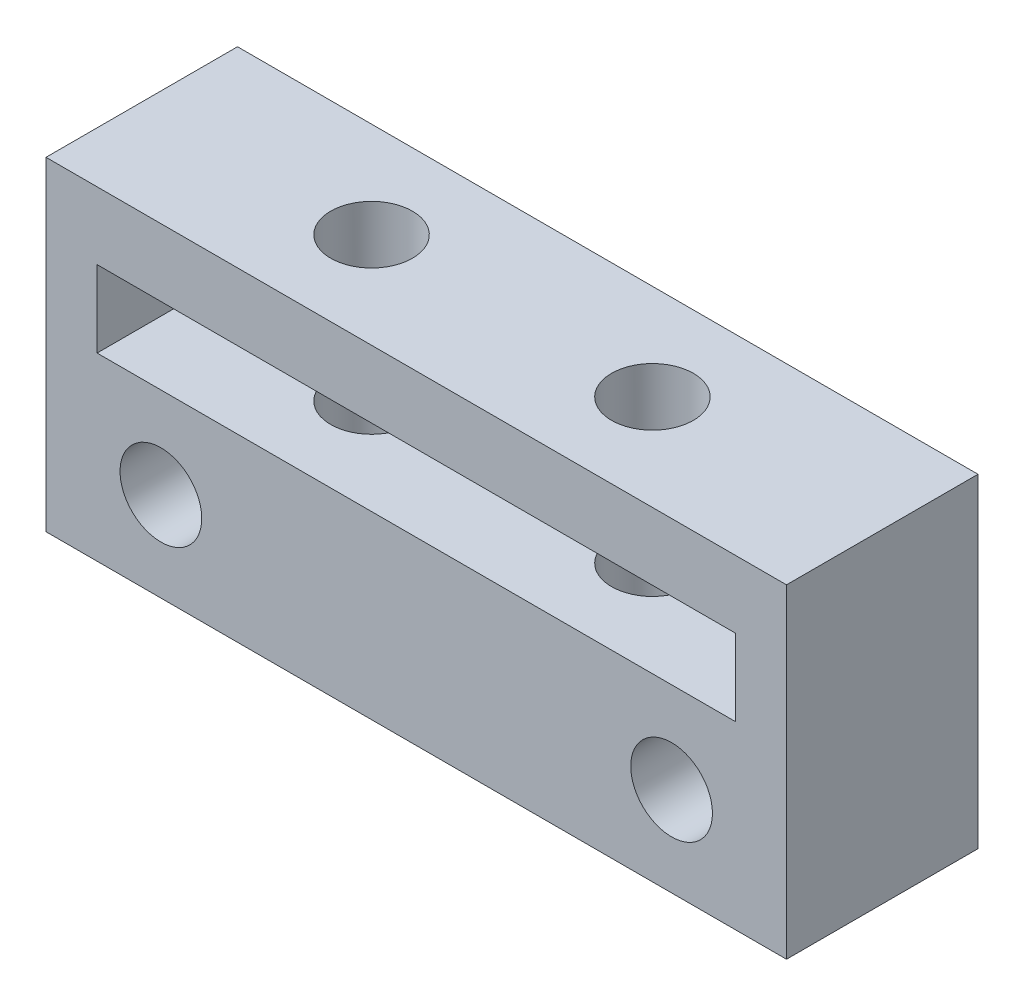
SolidWorks part; units mm, degrees
ref_plane "Front" through (0, 0, 0) normal (0, 0, 1) x (1, 0, 0)
ref_plane "Top" through (0, 0, 0) normal (0, 1, 0) x (1, 0, 0)
ref_plane "Right" through (0, 0, 0) normal (1, 0, 0) x (0, 0, -1)
sketch "草图1" plane through (0, 0, 0) normal (0, 0, 1) x (1, 0, 0)
  line L1 (-14.5, -9.6) -> (14.5, -9.6)
  line L2 (-14.5, -9.6) -> (-14.5, 9.6)
  line L3 (-14.5, 9.6) -> (14.5, 9.6)
  line L4 (14.5, -9.6) -> (14.5, 9.6)
  line L5 (-14.5, -9.6) -> (14.5, 9.6) construction
  line L6 (-14.5, 9.6) -> (14.5, -9.6) construction
  point P0 (0, 0)
  dimension "D1" = 19.2
  dimension "D2" = 29
extrude "凸台-拉伸1" add sketch "草图1" along normal blind 7.5
sketch "草图2" plane through (0, 0, 7.5) normal (0, 0, 1) x (1, 0, 0)
  line L1 (-14.5, 9.6) -> (-14.5, -9.6) construction
  line L2 (-14.5, -9.6) -> (14.5, -9.6) construction
  circle A2 centre (10, -6.1) radius 1.6
  circle A3 centre (-10, -6.1) radius 1.6
  point P0 (0, 0)
  point P8 (0, 0)
  point P9 (0, 0)
  point P10 (0, 0)
  point P11 (0, 0)
  point P12 (0, 0)
  point P19 (0, 0)
  point P20 (10, -6.1)
  dimension "D1" = 20
  dimension "D2" = 3.2
  dimension "D3" = 3.5
  dimension "D4" = 4.5
extrude "切除-拉伸1" cut sketch "草图2" against normal through all
sketch "草图3" plane through (0, 0, 7.5) normal (0, 0, 1) x (1, 0, 0)
  line L1 (-12.5, 0.4605) -> (12.5, 0.4605)
  line L2 (-12.5, 0.4605) -> (-12.5, -2.5395)
  line L3 (-12.5, -2.5395) -> (12.5, -2.5395)
  line L4 (12.5, 0.4605) -> (12.5, -2.5395)
  line L5 (-12.5, 0.4605) -> (12.5, -2.5395) construction
  line L6 (-12.5, -2.5395) -> (12.5, 0.4605) construction
  point P0 (0, -1.0395)
  point P6 (0, 0)
  point P7 (0, 0)
  point P8 (0, 0)
  point P9 (0, 0)
  point P10 (0, 0)
  point P11 (0, 0)
  point P12 (0, -1.0395)
  dimension "D1" = 25
  dimension "D2" = 3
extrude "切除-拉伸2" cut sketch "草图3" against normal blind 7.5
sketch "草图4" plane through (0, -9.6, 0) normal (0, -1, 0) x (1, 0, 0)
  line L0 (-5.5, 3.75) -> (5.5, 3.75) construction
  line L1 (-14.5, 0) -> (14.5, 0) construction
  line L2 (14.5, 7.5) -> (14.5, 0) construction
  circle A0 centre (-5.5, 3.75) radius 1.6
  circle A1 centre (5.5, 3.75) radius 1.6
  point P4 (0, 3.75)
  point P7 (0, 0)
  point P10 (14.5, 3.75)
  dimension "D1" = 3.2
  dimension "D2" = 3.2
  dimension "D3" = 0
  dimension "D4" = 0
  dimension "D5" = 11
extrude "切除-拉伸3" cut sketch "草图4" against normal through all
sketch "草图6" plane through (0, 0, 7.5) normal (0, 0, 1) x (1, 0, 0)
  line L0 (14.5, -9.6) -> (14.5, 9.6) construction
  line L1 (-14.5, 9.6) -> (-14.5, -9.6) construction
  line L2 (14.5, 9.6) -> (-14.5, 9.6) construction
  line L3 (14.5, 3.1) -> (14.5, 9.6)
  line L4 (-14.5, 9.6) -> (-14.5, 3.1)
  line L5 (14.5, 9.6) -> (-14.5, 9.6)
  line L6 (-14.5, 3.1) -> (14.5, 3.1)
  dimension "D1" = 6.5
extrude "切除-拉伸5" cut sketch "草图6" against normal through all
sketch "草图7" plane through (0, -9.6, 0) normal (0, -1, 0) x (1, 0, 0)
  circle A0 centre (5.5, 3.75) radius 1.6 construction
  circle A1 centre (-5.5, 3.75) radius 1.6 construction
  circle A2 centre (5.5, 3.75) radius 1.6
  circle A3 centre (-5.5, 3.75) radius 1.6
  circle A4 centre (-5.5, 3.75) radius 2.6
  circle A5 centre (5.5, 3.75) radius 2.6
  dimension "D1" = 1
extrude "切除-拉伸6" cut sketch "草图7" against normal blind 1.5
